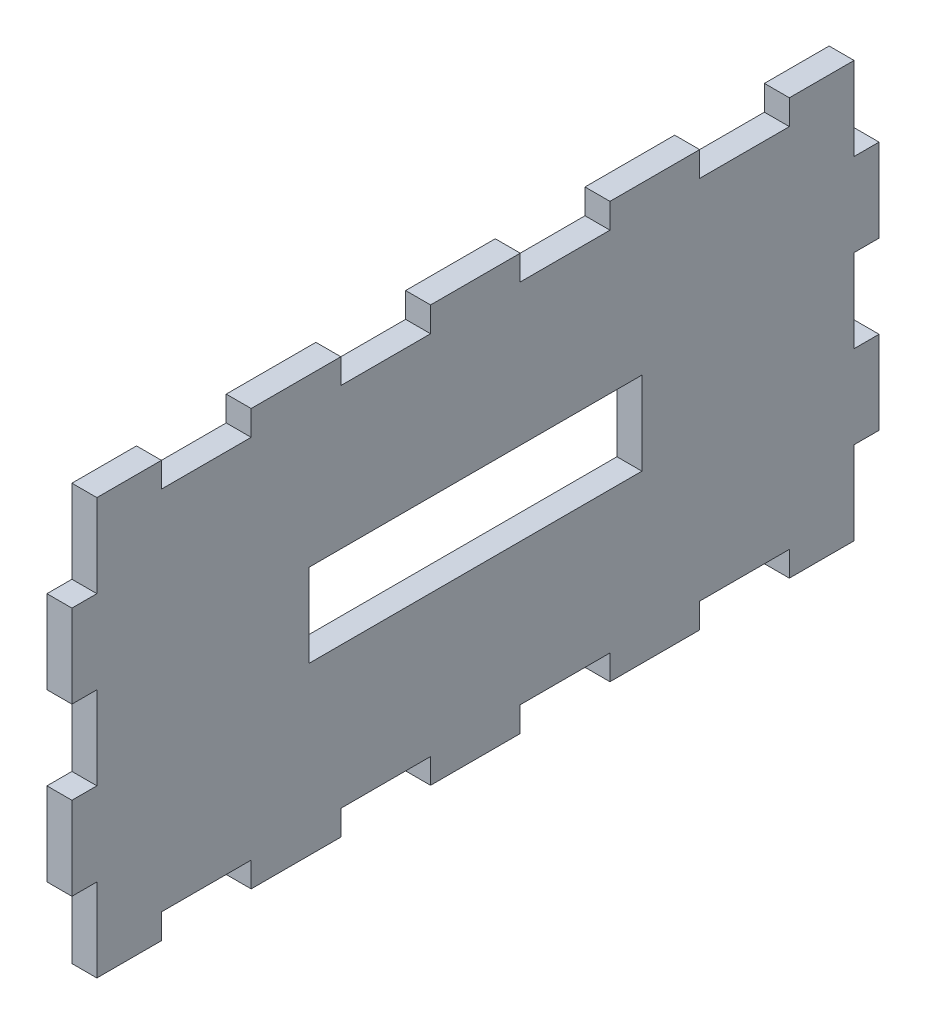
SolidWorks part; units mm, degrees
material "Balsa"
ref_plane "Front" through (0, 0, 0) normal (0, 0, 1) x (1, 0, 0)
ref_plane "Top" through (0, 0, 0) normal (0, 1, 0) x (1, 0, 0)
ref_plane "Right" through (0, 0, 0) normal (1, 0, 0) x (0, 0, -1)
sketch "Esboço1" plane through (0, 0, 0) normal (1, 0, 0) x (0, 0, -1)
  line L1 (48.5, -25) -> (-48.5, -25)
  line L2 (48.5, -25) -> (48.5, 25)
  line L3 (48.5, 25) -> (-48.5, 25)
  line L4 (-48.5, -25) -> (-48.5, 25)
  line L5 (48.5, -25) -> (-48.5, 25) construction
  line L6 (48.5, 25) -> (-48.5, -25) construction
  point P0 (0, 0)
  dimension "D1" = 97
  dimension "D2" = 50
extrude "Ressalto-extrusão1" add sketch "Esboço1" along normal blind 3
sketch "Esboço2" plane through (0, 0, 0) normal (-1, 0, 0) x (0, 0, 1)
  line L0 (-5.38, 22) -> (-16.1622, 22)
  line L1 (-26.94, 22) -> (-37.7222, 22)
  line L2 (-16.1622, 25) -> (-5.38, 25)
  line L3 (5.3978, 25) -> (16.18, 25)
  line L4 (-37.7222, 25) -> (-37.7222, 22)
  line L5 (-26.94, 25) -> (-26.94, 22)
  line L6 (16.18, 22) -> (5.3978, 22)
  line L7 (-16.1622, 25) -> (-16.1622, 22)
  line L8 (26.9578, 25) -> (37.74, 25)
  line L9 (-5.38, 25) -> (-5.38, 22)
  line L10 (-37.7222, -25) -> (-26.94, -25)
  line L11 (5.3978, 25) -> (5.3978, 22)
  line L12 (37.74, -22) -> (26.9578, -22)
  line L13 (16.18, 25) -> (16.18, 22)
  line L14 (-16.1622, -25) -> (-5.38, -25)
  line L15 (26.9578, 25) -> (26.9578, 22)
  line L16 (-26.94, -22) -> (-37.7222, -22)
  line L17 (37.74, 25) -> (37.74, 22)
  line L18 (5.3978, -25) -> (16.18, -25)
  line L19 (-5.38, -22) -> (-16.1622, -22)
  line L20 (26.9578, -25) -> (37.74, -25)
  line L21 (-26.94, -22) -> (-26.94, -25)
  line L22 (16.18, -22) -> (5.3978, -22)
  line L23 (-16.1622, -22) -> (-16.1622, -25)
  line L25 (-5.38, -22) -> (-5.38, -25)
  line L27 (5.3978, -22) -> (5.3978, -25)
  line L29 (16.18, -22) -> (16.18, -25)
  line L31 (26.9578, -22) -> (26.9578, -25)
  line L33 (37.74, -22) -> (37.74, -25)
  line L39 (-37.7222, -22) -> (-37.7222, -25)
  line L40 (-37.7222, 25) -> (-26.94, 25)
  line L41 (37.74, 22) -> (26.9578, 22)
  line L43 (48.5178, 25) -> (48.5178, 22) [skipped]
  line L44 (48.5178, -22) -> (48.5178, -25) [skipped]
  dimension "D1" = 3
  dimension "D3" = 5
  dimension "D4" = 2
extrude "Corte-extrusão1" cut sketch "Esboço2" against normal up to next
sketch "Esboço3" plane through (0, 0, 0) normal (1, 0, 0) x (0, 0, -1)
  line L1 (20, 5) -> (-20, 5)
  line L2 (20, 5) -> (20, -5)
  line L3 (20, -5) -> (-20, -5)
  line L4 (-20, 5) -> (-20, -5)
  line L5 (20, 5) -> (-20, -5) construction
  line L6 (20, -5) -> (-20, 5) construction
  point P0 (0, 0)
  point P1 (0, 0)
  point P5 (0, 0)
  dimension "D1" = 40
  dimension "D2" = 10
sketch "Esboço4" plane through (0, 0, 0) normal (-1, 0, 0) x (0, 0, 1)
  line L0 (48.5, 25) -> (48.5, 15)
  line L2 (-45.5, -15) -> (-45.5, -25)
  line L3 (-48.5, 15) -> (-45.5, 15)
  line L4 (-45.5, 25) -> (-45.5, 15)
  line L5 (48.5, -25) -> (45.5, -25)
  line L6 (45.5, 15) -> (48.5, 15)
  line L7 (48.5, -25) -> (37.74, -25) construction
  line L8 (45.5, 5) -> (48.5, 5)
  line L9 (45.5, -25) -> (45.5, -15)
  line L10 (45.5, -5) -> (48.5, -5)
  line L11 (37.74, 25) -> (48.5, 25) construction
  line L12 (45.5, -15) -> (48.5, -15)
  line L13 (45.5, -5) -> (45.5, 5)
  line L14 (45.5, 25) -> (48.5, 25)
  line L15 (48.5, 5) -> (48.5, -5)
  line L16 (-48.5, 5) -> (-45.5, 5)
  line L17 (45.5, 15) -> (45.5, 25)
  line L18 (-48.5, -5) -> (-45.5, -5)
  line L19 (48.5, -15) -> (48.5, -25)
  line L20 (-48.5, -15) -> (-45.5, -15)
  line L21 (-48.5, 25) -> (-37.7222, 25) construction
  line L22 (-37.7222, -25) -> (-48.5, -25) construction
  line L23 (-45.5, -25) -> (-48.5, -25)
  line L26 (-48.5, -25) -> (-48.5, -15)
  line L27 (-48.5, 25) -> (-45.5, 25)
  line L28 (-45.5, 5) -> (-45.5, -5)
  line L29 (-48.5, -25) -> (-45.5, -25) [skipped]
  line L30 (45.5, -25) -> (48.5, -25) [skipped]
  line L31 (-48.5, 15) -> (-48.5, 25)
  line L32 (-48.5, -5) -> (-48.5, 5)
  dimension "D1" = 3
  dimension "D3" = 2
  dimension "D4" = 3
extrude "Corte-extrusão2" cut sketch "Esboço4" against normal up to next
extrude "Corte-extrusão5" cut sketch "Esboço3" along normal up to next
